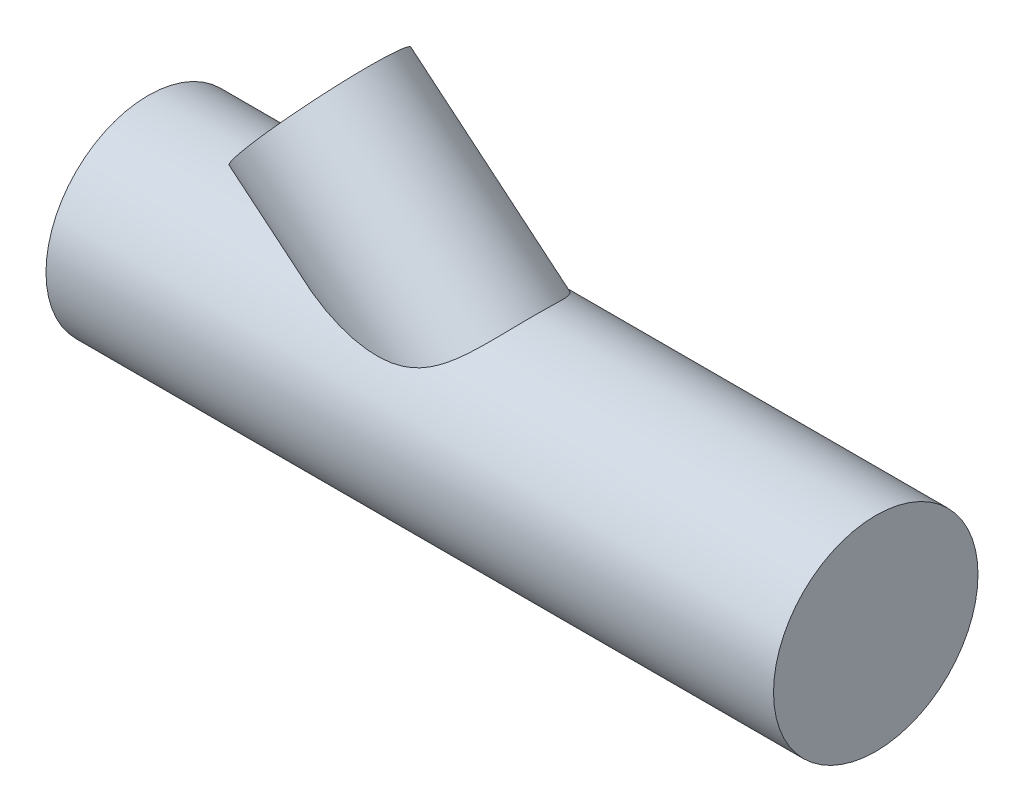
SolidWorks part; units mm, degrees
ref_plane "前视基准面" through (0, 0, 0) normal (0, 0, 1) x (1, 0, 0)
ref_plane "上视基准面" through (0, 0, 0) normal (0, 1, 0) x (1, 0, 0)
ref_plane "右视基准面" through (0, 0, 0) normal (1, 0, 0) x (0, 0, -1)
other "Configuration Table"
sketch "草图2" plane through (34.8544, -17.173, 0) normal (0, 0, 1) x (1, 0, 0)
  line L0 (-104.1784, 28.4033) -> (38.1378, 28.4033)
revolve "旋转-薄壁1" add sketch "草图2" angle 360 about L0 wall 20
sketch "草图3" plane through (10.6371, -26.3, 0) normal (0, 0, 1) x (1, 0, 0)
  line L0 (-46.3842, 72.519) -> (1.1569, 32.9691)
revolve "旋转-薄壁2" add sketch "草图3" angle 360 about L0 wall 15
